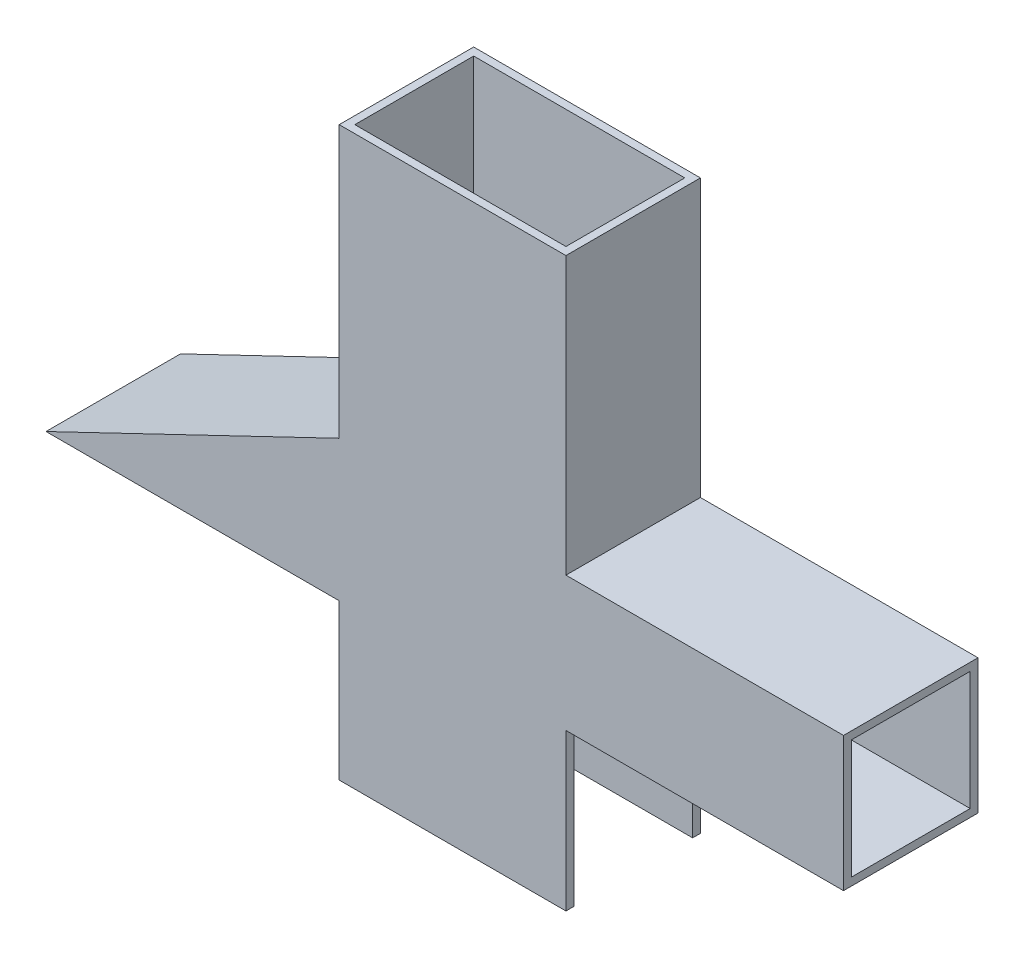
SolidWorks part; units mm, degrees
ref_plane "Plan de face" through (0, 0, 0) normal (0, 0, 1) x (1, 0, 0)
ref_plane "Plan de dessus" through (0, 0, 0) normal (0, 1, 0) x (1, 0, 0)
ref_plane "Plan de droite" through (0, 0, 0) normal (1, 0, 0) x (0, 0, -1)
sketch "Esquisse1" plane through (0, 0, 0) normal (0, 1, 0) x (1, 0, 0)
  line L1 (-37.701, 15.9512) -> (107.299, 15.9512)
  line L2 (-37.701, 15.9512) -> (-37.701, -70.0488)
  line L3 (-37.701, -70.0488) -> (107.299, -70.0488)
  line L4 (107.299, 15.9512) -> (107.299, -70.0488)
  line L5 (-32.701, 10.9512) -> (102.299, 10.9512)
  line L6 (-32.701, 10.9512) -> (-32.701, -65.0488)
  line L7 (-32.701, -65.0488) -> (102.299, -65.0488)
  line L8 (102.299, 10.9512) -> (102.299, -65.0488)
  dimension "D1" = 145
  dimension "D2" = 86
  dimension "D3" = 5
  dimension "D4" = 5
  dimension "D5" = 5
  dimension "D6" = 5
extrude "Boss.-Extru.1" add sketch "Esquisse1" along normal blind 258
sketch "Esquisse2" plane through (0, 0, 0) normal (0, -1, 0) x (1, 0, 0)
  line L1 (-37.701, 70.0488) -> (107.299, 70.0488)
  line L2 (-37.701, 70.0488) -> (-37.701, -15.9512)
  line L3 (-37.701, -15.9512) -> (107.299, -15.9512)
  line L4 (107.299, 70.0488) -> (107.299, -15.9512)
extrude "Boss.-Extru.2" add sketch "Esquisse2" along normal blind 5
sketch "Esquisse3" plane through (0, -5, 0) normal (0, -1, 0) x (1, 0, 0)
  line L0 (102.299, -10.9512) -> (-32.701, -10.9512) construction
  line L1 (-32.701, 65.0488) -> (-2.701, 65.0488)
  line L2 (-32.701, 65.0488) -> (-32.701, -10.9512)
  line L3 (-32.701, -10.9512) -> (-2.701, -10.9512)
  line L4 (-2.701, 65.0488) -> (-2.701, -10.9512)
  dimension "D1" = 30
extrude "Enlèv. mat.-Extru.1" cut sketch "Esquisse3" against normal blind 5
sketch "Esquisse5" plane through (0, -5, 0) normal (0, -1, 0) x (1, 0, 0)
  line L0 (-37.701, -15.9512) -> (107.299, -15.9512) construction
  line L1 (-37.701, 70.0488) -> (-32.701, 70.0488)
  line L2 (-37.701, 70.0488) -> (-37.701, -15.9512)
  line L3 (-37.701, -15.9512) -> (-32.701, -15.9512)
  line L4 (-32.701, 70.0488) -> (-32.701, -15.9512)
  dimension "D1" = 5
extrude "Boss.-Extru.3" add sketch "Esquisse5" along normal blind 100
sketch "Esquisse9" plane through (0, 0, 70.0488) normal (0, 0, 1) x (1, 0, 0)
  line L0 (-37.701, -5.7005) -> (-37.701, 84.2995)
  line L1 (-37.701, 258) -> (-37.701, -105) construction
  line L2 (-37.701, 84.2995) -> (-225.201, -5.7005)
  line L3 (-225.201, -5.7005) -> (-37.701, -5.7005)
  dimension "D1" = 90
  dimension "D2" = 187.5
extrude "Boss.-Extru.6" add sketch "Esquisse9" against normal blind 86
sketch "Esquisse10" plane through (107.299, 0, 0) normal (1, 0, 0) x (0, 0, -1)
  line L0 (-70.0488, 258) -> (-70.0488, -5) construction
  line L1 (-70.0488, 81) -> (15.9512, 81)
  line L2 (-70.0488, 81) -> (-70.0488, -5)
  line L3 (-70.0488, -5) -> (15.9512, -5)
  line L4 (15.9512, 81) -> (15.9512, -5)
  line L6 (-65.0488, 76) -> (10.9512, 76)
  line L7 (-65.0488, 76) -> (-65.0488, 0)
  line L8 (-65.0488, 0) -> (10.9512, 0)
  line L9 (10.9512, 76) -> (10.9512, 0)
  dimension "D1" = 76
  dimension "D2" = 5
  dimension "D3" = 5
  dimension "D4" = 5
  dimension "D5" = 5
extrude "Boss.-Extru.7" add sketch "Esquisse10" along normal blind 177.5
sketch "Esquisse11" plane through (107.299, 0, 0) normal (1, 0, 0) x (0, 0, -1)
  line L1 (-65.0488, 76) -> (10.9512, 76)
  line L2 (-65.0488, 76) -> (-65.0488, 0)
  line L3 (-65.0488, 0) -> (10.9512, 0)
  line L4 (10.9512, 76) -> (10.9512, 0)
extrude "Enlèv. mat.-Extru.2" cut sketch "Esquisse11" against normal blind 10
sketch "Esquisse12" plane through (0, -5, 0) normal (0, -1, 0) x (1, 0, 0)
  line L0 (-32.701, -15.9512) -> (284.799, -15.9512) construction
  line L1 (-32.701, 70.0488) -> (107.299, 70.0488)
  line L2 (-32.701, 70.0488) -> (-32.701, 65.0488)
  line L3 (-32.701, 65.0488) -> (107.299, 65.0488)
  line L4 (107.299, 70.0488) -> (107.299, 65.0488)
  line L5 (-32.701, -10.9512) -> (107.299, -10.9512)
  line L6 (-32.701, -10.9512) -> (-32.701, -15.9512)
  line L7 (-32.701, -15.9512) -> (107.299, -15.9512)
  line L8 (107.299, -10.9512) -> (107.299, -15.9512)
  dimension "D1" = 5
  dimension "D2" = 5
  dimension "D3" = 140
  dimension "D4" = 140
extrude "Boss.-Extru.8" add sketch "Esquisse12" along normal blind 100
